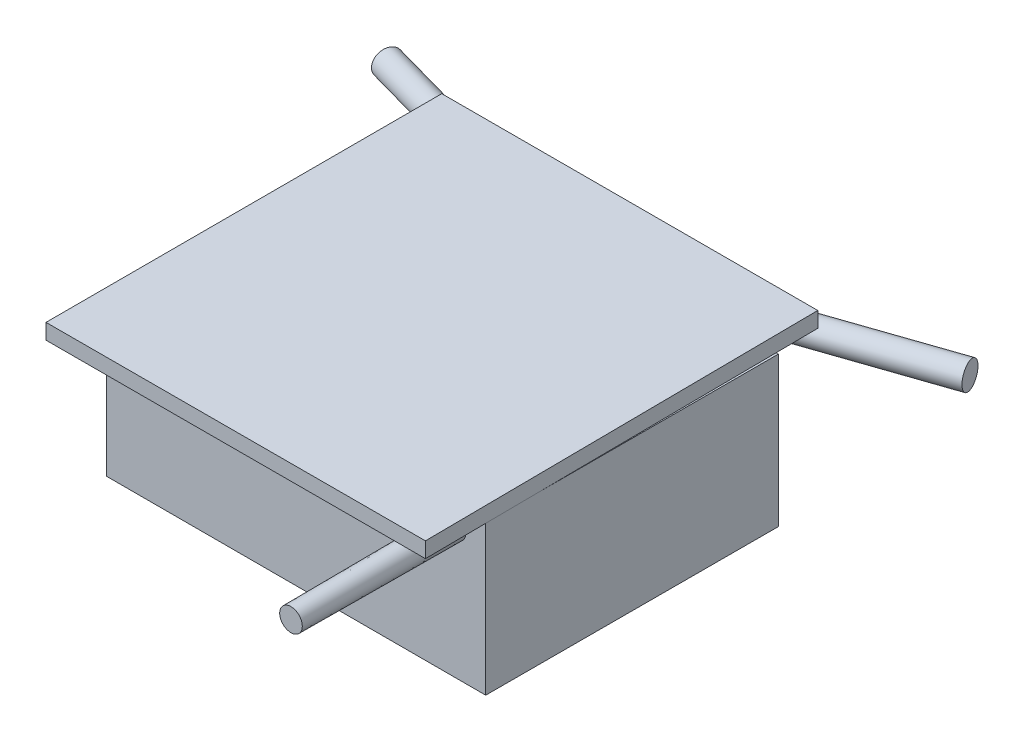
SolidWorks part; units mm, degrees
ref_plane "前视基准面" through (0, 0, 0) normal (0, 0, 1) x (1, 0, 0)
ref_plane "上视基准面" through (0, 0, 0) normal (0, 1, 0) x (1, 0, 0)
ref_plane "右视基准面" through (0, 0, 0) normal (1, 0, 0) x (0, 0, -1)
sketch "草图1" plane through (0, 0, 0) normal (0, 1, 0) x (1, 0, 0)
  line L0 (0, 567.3554) -> (0, -565.0604) construction
  line L1 (-828.1018, 0) -> (841.6643, 0) construction
  line L5 (368, -264) -> (-368, -264)
  line L11 (-367, 301) -> (368.6, 303.3)
  line L12 (-367, 301) -> (-368, -264)
  line L13 (368.6, 303.3) -> (368, -264)
extrude "凸台-拉伸1" add sketch "草图1" along normal blind 320
sketch "草图2" plane through (0, 320, 0) normal (0, 1, 0) x (1, 0, 0)
  line L0 (-478.2848, 0) -> (491.6339, 0) construction
  line L1 (0, 514.3838) -> (0, -467.3965) construction
  line L4 (363.5, 385) -> (370, -383)
  line L5 (-365.8, 384.5) -> (-365.5, -384)
  line L8 (-365.8, 384.5) -> (363.5, 385)
  line L9 (-365.5, -384) -> (370, -383)
extrude "凸台-拉伸2" add sketch "草图2" against normal blind 30 contours L5 L9 L4 L8
sketch "草图3" plane through (0, 320, 0) normal (0, 1, 0) x (1, 0, 0)
  line L0 (364.1916, 303.2862) -> (368.1103, -159.7232)
  line L1 (-365.7674, 301.0039) -> (-365.5468, -264)
  line L2 (368.1103, -159.7232) -> (368.6, 303.3) construction
  line L3 (368.6, 303.3) -> (364.1916, 303.2862) construction
  line L4 (-368, -264) -> (-365.5468, -264) construction
  line L5 (-365.7674, 301.0039) -> (-367, 301) construction
  line L6 (-367, 301) -> (-368, -264) construction
  line L7 (368.1103, -159.7232) -> (368.6, 303.3)
  line L8 (368.6, 303.3) -> (364.1916, 303.2862)
  line L9 (-368, -264) -> (-365.5468, -264)
  line L10 (-365.7674, 301.0039) -> (-367, 301)
  line L11 (-367, 301) -> (-368, -264)
extrude "切除-拉伸1" cut sketch "草图3" against normal up to surface (30 mm away) up to face at (75.0127, 290, 290.9446)
sketch "草图4" plane through (0, 0, 0) normal (0, 0, 1) x (1, 0, 0)
  line L0 (0, 396.5114) -> (0, -74.3295) construction
  line L2 (-368, 0) -> (368, 0) construction
  circle A0 centre (306, 254) radius 25
  dimension "D3" = 50
  dimension "D1" = 306
  dimension "D2" = 254
extrude "凸台-拉伸3" add sketch "草图4" along normal blind 580 draft 0.3
ref_plane "基准面2" through (0, 254, 0) normal (0, -1, 0) x (-1, 0, 0)
sketch "草图5" plane through (0, 254, 0) normal (0, -1, 0) x (-1, 0, 0)
  line L5 (537, 450) -> (0, 300)
sketch "草图7" plane through (0, 254, 0) normal (0, -1, 0) x (-1, 0, 0)
  line L3 (-554, 490) -> (0, 300)
ref_plane "基准面3" through (0, 254, -300) normal (0.9631, 0, 0.269) x (0.269, 0, -0.9631)
sketch "草图8" plane through (0, 254, -300) normal (0.9631, 0, 0.269) x (0.269, 0, -0.9631)
  circle A0 centre (0, 0) radius 25
  dimension "D1" = 50
extrude "凸台-拉伸4" add sketch "草图8" against normal up to vertex (557.5563 mm away) up to point (-537, 254, -450)
ref_plane "基准面4" through (0, 254, -300) normal (-0.9459, 0, 0.3244) x (0.3244, 0, 0.9459)
sketch "草图9" plane through (0, 254, -300) normal (-0.9459, 0, 0.3244) x (0.3244, 0, 0.9459)
  circle A0 centre (0, 0) radius 25
  dimension "D1" = 50
extrude "凸台-拉伸5" add sketch "草图9" against normal up to vertex (585.6757 mm away) up to point (554, 254, -490)
sketch3d "3D草图1"
  line L0 (-537, 254, -450) -> (-0.6142, 254, -300.1716) construction
  line L1 (306, 254, 264) -> (306, 254, 580) construction
  line L2 (554, 254, -490) -> (0.6032, 254, -300.2069) construction
  point P0 (-537, 254, -450)
  point P1 (306, 254, 580)
  point P4 (554, 254, -490)
  point P7 (-365.5, 320, 384)
  point P10 (370, 320, 383)
  point P12 (363.5, 320, -385)
  point P14 (-365.8, 320, -384.5)
  point P16 (-367, 0, -301)
  point P18 (-368, 0, 264)
  point P20 (368, 0, 264)
  point P22 (368.6, 0, -303.3)
  point P26 (0, 0, 0)
